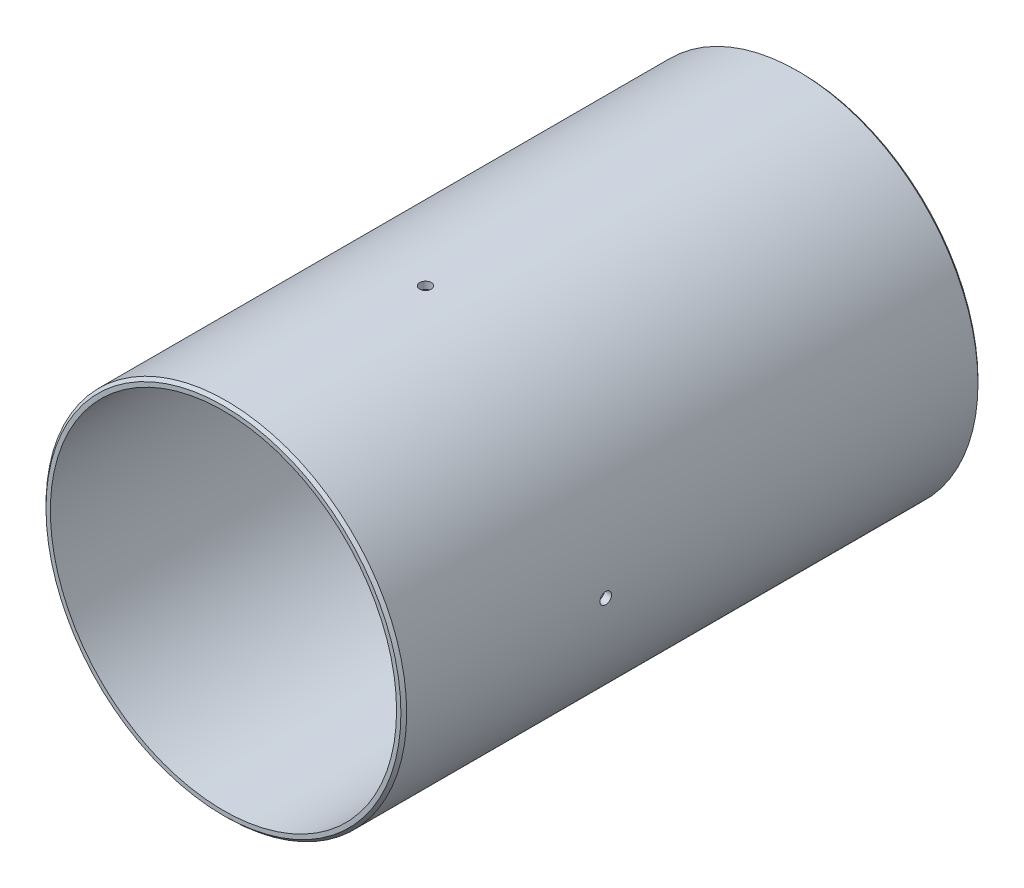
SolidWorks part; units mm, degrees
material "E-Glass Fiber"
ref_plane "Ön Düzlem" through (0, 0, 0) normal (0, 0, 1) x (1, 0, 0)
ref_plane "Üst Düzlem" through (0, 0, 0) normal (0, 1, 0) x (1, 0, 0)
ref_plane "Sağ Düzlem" through (0, 0, 0) normal (1, 0, 0) x (0, 0, -1)
sketch "Sketch1" plane through (0, 0, 0) normal (0, 0, 1) x (1, 0, 0)
  circle A0 centre (0, 0) radius 62.5
  circle A1 centre (0, 0) radius 60
  dimension "D1" = 125
  dimension "D2" = 2.5
extrude "Boss-Extrude1" add sketch "Sketch1" along normal mid plane 200
sketch "Sketch2" plane through (0, 0, 0) normal (0, 1, 0) x (1, 0, 0)
  line L0 (0, 100) -> (0, -30) construction
  line L3 (62.5, 100) -> (-62.5, 100) construction
  line L4 (0, -30) -> (0, -100) construction
  line L5 (-62.5, -100) -> (62.5, -100) construction
  circle A0 centre (0, -30) radius 2
  dimension "D2" = 4
  dimension "D1" = 70
extrude "Cut-Extrude1" cut sketch "Sketch2" against normal mid plane 200
sketch "Sketch3" plane through (0, 0, 0) normal (1, 0, 0) x (0, 0, -1)
  line L0 (-100, 0) -> (-30, 0) construction
  line L1 (-100, 62.5) -> (-100, -62.5) construction
  line L2 (-30, 0) -> (100, 0) construction
  line L3 (100, -62.5) -> (100, 62.5) construction
  circle A0 centre (-30, 0) radius 2
  dimension "D2" = 4
  dimension "D1" = 70
extrude "Cut-Extrude2" cut sketch "Sketch3" against normal mid plane 148
chamfer "Chamfer1" distance 1 angle 45 1 edges at (62.5, 0, 100)
chamfer "Chamfer2" distance 1 angle 45 1 edges at (62.5, 0, -100)
